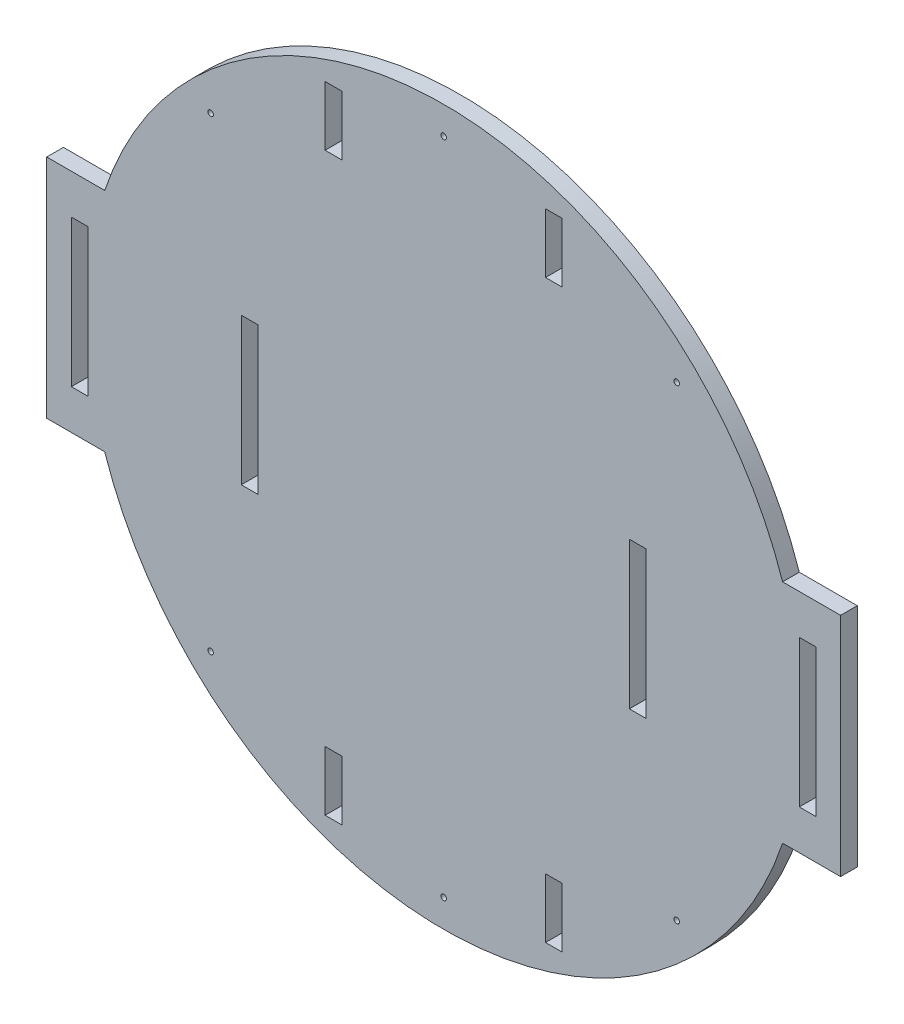
SolidWorks part; units mm, degrees
ref_plane "Front Plane" through (0, 0, 0) normal (0, 0, 1) x (1, 0, 0)
ref_plane "Top Plane" through (0, 0, 0) normal (0, 1, 0) x (1, 0, 0)
ref_plane "Right Plane" through (0, 0, 0) normal (1, 0, 0) x (0, 0, -1)
sketch "Sketch1" plane through (0, 0, 0) normal (0, 0, 1) x (1, 0, 0)
  line L0 (0, 0) -> (0, 114.3) construction
  line L1 (126.9598, -36.195) -> (108.4178, -36.195)
  line L2 (-126.9598, 36.195) -> (-108.4178, 36.195)
  line L3 (-126.9598, 36.195) -> (-126.9598, -36.195)
  line L4 (-126.9598, -36.195) -> (-108.4178, -36.195)
  line L5 (126.9598, 36.195) -> (126.9598, -36.195)
  line L6 (126.9598, 36.195) -> (108.4178, 36.195)
  line L7 (-126.9598, 23.495) -> (-113.7518, 23.495) construction
  line L8 (-108.4178, 23.495) -> (-108.4178, 36.195) construction
  line L10 (-113.7518, 23.495) -> (-113.7518, -23.495) construction
  line L11 (-113.7518, 23.495) -> (-119.0858, 23.495)
  line L12 (-113.7518, 23.495) -> (-113.7518, -23.495)
  line L13 (-108.4178, -23.495) -> (-108.4178, -36.195) construction
  line L14 (113.7518, -23.495) -> (108.4178, -23.495) construction
  line L15 (113.7518, 23.495) -> (108.4178, 23.495) construction
  line L16 (113.7518, 23.495) -> (113.7518, -23.495) construction
  line L17 (-113.7518, -23.495) -> (-119.0858, -23.495)
  line L18 (-108.4178, 23.495) -> (-64.7298, 23.495) construction
  line L19 (64.7298, 23.495) -> (64.7298, -23.495)
  line L20 (-64.7298, 23.495) -> (-59.3958, 23.495)
  line L21 (-64.7298, 23.495) -> (-64.7298, -23.495)
  line L22 (-64.7298, -23.495) -> (-59.3958, -23.495)
  line L23 (-59.3958, 23.495) -> (-59.3958, -23.495)
  line L24 (59.3958, 23.495) -> (59.3958, -23.495)
  line L25 (64.7298, -23.495) -> (59.3958, -23.495)
  line L26 (64.7298, 23.495) -> (59.3958, 23.495)
  line L27 (108.4178, 36.195) -> (108.4178, -36.195) construction
  line L28 (113.7518, 23.495) -> (119.0858, 23.495)
  line L29 (113.7518, 23.495) -> (113.7518, -23.495)
  line L30 (113.7518, -23.495) -> (119.0858, -23.495)
  line L31 (119.0858, 23.495) -> (119.0858, -23.495)
  line L32 (-119.0858, 23.495) -> (-119.0858, -23.495)
  arc A0 (-108.4178, -36.195) -> (108.4178, -36.195) centre (0, 0) ccw
  arc A1 (108.4178, 36.195) -> (-108.4178, 36.195) centre (0, 0) ccw
  dimension "D1" = 228.6
  dimension "D2" = 72.39
  dimension "D3" = 13.208
  dimension "D4" = 5.334
  dimension "D5" = 46.99
  dimension "D6" = 12.7
  dimension "D7" = 43.688
  dimension "D8" = 5.334
  dimension "D9" = 5.334
  dimension "D10" = 5.334
  dimension "D11" = 5.334
extrude "Base Platform" add sketch "Sketch1" along normal blind 5.334
sketch "Sketch5" plane through (0, 0, 0) normal (0, 0, -1) x (-1, 0, 0)
  line L0 (0, 0) -> (0, -105.41) construction
  circle A1 centre (0, 105.41) radius 0.889
  circle A4 centre (0, -105.41) radius 0.889
  circle A5 centre (-74.5361, 74.5361) radius 0.889
  circle A6 centre (74.5361, 74.5361) radius 0.889
  circle A7 centre (74.5361, -74.5361) radius 0.889
  circle A8 centre (-74.5361, -74.5361) radius 0.889
  dimension "D1" = 1.778
  dimension "D3" = 1.778
  dimension "D4" = 1.778
  dimension "D5" = 1.778
  dimension "D6" = 1.778
  dimension "D7" = 1.778
extrude "Perimeter stacking cuts" cut sketch "Sketch5" against normal blind 5.334
sketch "Sketch6" plane through (0, 0, 0) normal (0, 0, -1) x (-1, 0, 0)
  line L4 (-32.5846, 82.5804) -> (-37.9186, 82.5804)
  line L5 (-32.5846, 82.5804) -> (-32.5846, 101.6304)
  line L6 (-32.5846, 101.6304) -> (-37.9186, 101.6304)
  line L7 (-37.9186, 82.5804) -> (-37.9186, 101.6304)
  line L8 (32.5846, 82.5804) -> (37.9186, 82.5804)
  line L9 (32.5846, 82.5804) -> (32.5846, 101.6304)
  line L10 (32.5846, 101.6304) -> (37.9186, 101.6304)
  line L11 (37.9186, 82.5804) -> (37.9186, 101.6304)
  line L17 (37.9186, -82.5804) -> (37.9186, -101.6304)
  line L18 (32.5846, -101.6304) -> (37.9186, -101.6304)
  line L19 (32.5846, -82.5804) -> (32.5846, -101.6304)
  line L20 (32.5846, -82.5804) -> (37.9186, -82.5804)
  line L21 (-37.9186, -82.5804) -> (-37.9186, -101.6304)
  line L22 (-32.5846, -101.6304) -> (-37.9186, -101.6304)
  line L23 (-32.5846, -82.5804) -> (-32.5846, -101.6304)
  line L24 (-32.5846, -82.5804) -> (-37.9186, -82.5804)
  dimension "D1" = 19.05
  dimension "D2" = 5.334
  dimension "D3" = 5.334
  dimension "D4" = 19.05
  dimension "D5" = 19.05
  dimension "D6" = 5.334
  dimension "D7" = 19.05
  dimension "D8" = 5.334
extrude "Skid Holes" cut sketch "Sketch6" against normal blind 5.334
